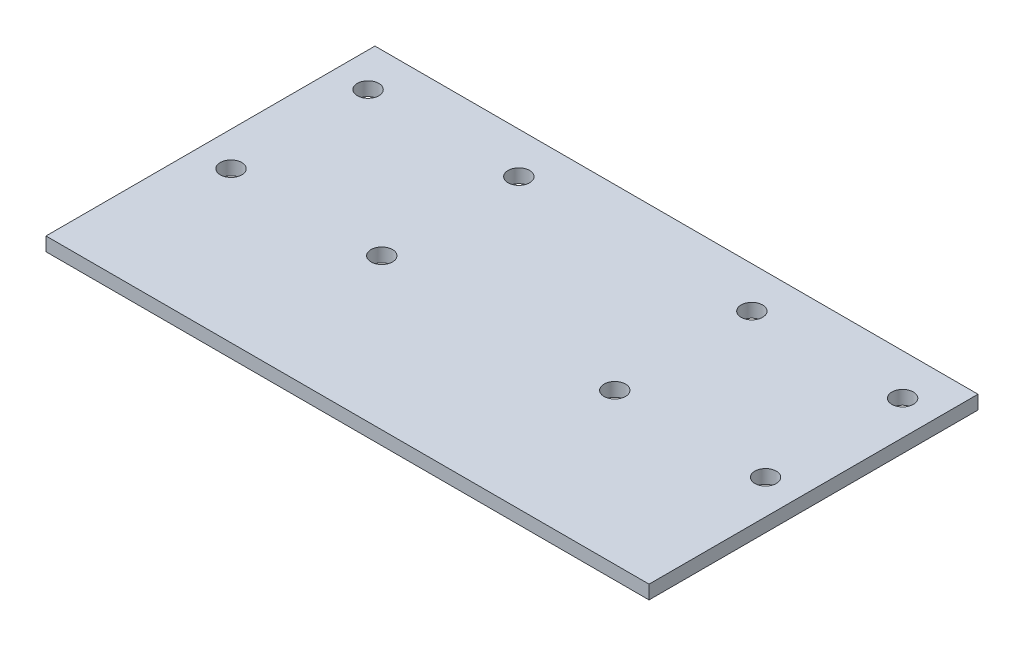
SolidWorks part; units mm, degrees
ref_plane "Front Plane" through (0, 0, 0) normal (0, 0, 1) x (1, 0, 0)
ref_plane "Top Plane" through (0, 0, 0) normal (0, 1, 0) x (1, 0, 0)
ref_plane "Right Plane" through (0, 0, 0) normal (1, 0, 0) x (0, 0, -1)
sketch "Sketch1" plane through (0, 0, 0) normal (0, 1, 0) x (1, 0, 0)
  line L1 (-69.85, -38.1) -> (69.85, -38.1)
  line L2 (-69.85, -38.1) -> (-69.85, 38.1)
  line L3 (-69.85, 38.1) -> (69.85, 38.1)
  line L4 (69.85, -38.1) -> (69.85, 38.1)
  line L5 (-69.85, -38.1) -> (69.85, 38.1) construction
  line L6 (-69.85, 38.1) -> (69.85, -38.1) construction
  point P0 (0, 0)
  dimension "D1" = 76.2
  dimension "D2" = 139.7
extrude "Boss-Extrude1" add sketch "Sketch1" along normal blind 3.175
sketch "Sketch2" plane through (0, 3.175, 0) normal (0, 1, 0) x (1, 0, 0)
  line L0 (-61.9125, -3.175) -> (61.9125, -3.175) construction
  line L1 (-61.9125, -3.175) -> (-61.9125, 28.575) construction
  line L2 (61.9125, -3.175) -> (61.9125, 28.575) construction
  line L3 (0, -3.175) -> (0, 0) construction
  line L4 (-69.85, -38.1) -> (69.85, -38.1) construction
  point P5 (-61.9125, -3.175)
  point P6 (-61.9125, 28.575)
  point P7 (61.9125, -3.175)
  point P8 (61.9125, 28.575)
  point P9 (-26.9875, -3.175)
  point P10 (26.9875, -3.175)
  point P11 (26.9875, 28.575)
  point P12 (-26.9875, 28.575)
  point P15 (0, 0)
  dimension "D1" = 123.825
  dimension "D2" = 31.75
  dimension "D3" = 53.975
  dimension "D4" = 34.925
hole_wizard "#10 Clearance Hole1" positions "Sketch3" profile "Sketch4" hole size "#10" standard "ANSI Inch"
sketch "Sketch3" plane through (0, 3.175, 0) normal (0, 1, 0) x (1, 0, 0)
  point P0 (-61.9125, 28.575)
  point P3 (-61.9125, -3.175)
  point P6 (-26.9875, -3.175)
  point P9 (-26.9875, 28.575)
  point P12 (26.9875, 28.575)
  point P15 (61.9125, 28.575)
  point P18 (61.9125, -3.175)
  point P21 (26.9875, -3.175)
sketch "Sketch4" plane through (-61.9125, 3.175, -28.575) normal (1, 0, 0) x (0, 0, 1)
  line L0 (0, 0) -> (0, 7.8457)
  line L1 (0, 7.8457) -> (2.4892, 6.35)
  line L2 (2.4892, 6.35) -> (2.4892, 0)
  line L5 (2.4892, 0) -> (0, 0)
  line L10 (0, 7.8457) -> (-2.4892, 6.35) construction
  line L11 (0, -6.35) -> (0, 107.95) construction
  dimension "Hole Dia." = 4.9784
  dimension "Hole Depth" = 6.35
  dimension "Drill Angle" = 118
